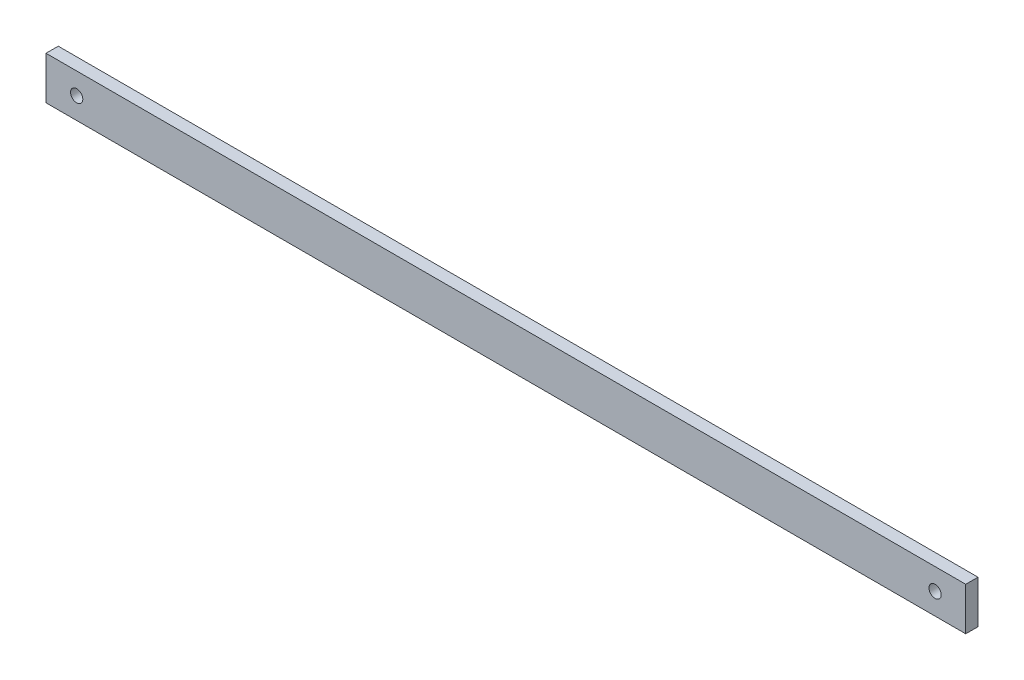
SolidWorks part; units mm, degrees
ref_plane "Front Plane" through (0, 0, 0) normal (0, 0, 1) x (1, 0, 0)
ref_plane "Top Plane" through (0, 0, 0) normal (0, 1, 0) x (1, 0, 0)
ref_plane "Right Plane" through (0, 0, 0) normal (1, 0, 0) x (0, 0, -1)
sketch "Sketch1" plane through (0, 0, 0) normal (0, 0, 1) x (1, 0, 0)
  line L0 (-75, 0) -> (75, 0) construction
  line L1 (-75, -3.5) -> (75, -3.5)
  line L2 (-75, -3.5) -> (-75, 3.5)
  line L3 (-75, 3.5) -> (75, 3.5)
  line L4 (75, -3.5) -> (75, 3.5)
  line L5 (0, 3.5) -> (0, -3.5) construction
  line L6 (-75, 3.5) -> (75, -3.5) construction
  line L7 (-75, -3.5) -> (75, 3.5) construction
  circle A0 centre (-70, 0) radius 1
  circle A1 centre (70, 0) radius 1
  point P0 (0, 0)
  dimension "D4" = 2
  dimension "D1" = 7
  dimension "D2" = 150
  dimension "D3" = 5
extrude "Boss-Extrude1" add sketch "Sketch1" along normal blind 2
